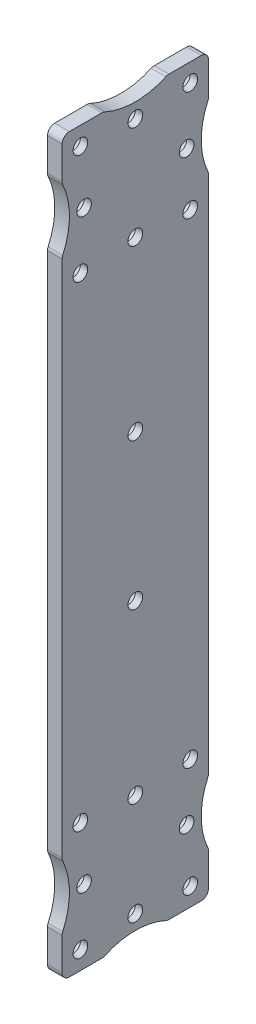
SolidWorks part; units mm, degrees
ref_plane "前视基准面" through (0, 0, 0) normal (0, 0, 1) x (1, 0, 0)
ref_plane "上视基准面" through (0, 0, 0) normal (0, 1, 0) x (1, 0, 0)
ref_plane "右视基准面" through (0, 0, 0) normal (1, 0, 0) x (0, 0, -1)
sketch "草图1" plane through (0, 0, 0) normal (1, 0, 0) x (0, 0, -1)
  line L0 (0, 50) -> (20, 50) construction
  line L1 (0, 0) -> (20, 0)
  line L2 (0, 0) -> (0, 100)
  line L3 (0, 100) -> (20, 100)
  line L4 (20, 0) -> (20, 100)
  circle A0 centre (2.5, 97.5) radius 1
  circle A1 centre (17.5, 97.5) radius 1
  circle A2 centre (17.5, 82.5) radius 1
  circle A3 centre (2.5, 82.5) radius 1
  circle A4 centre (17.5, 17.5) radius 1
  circle A5 centre (2.5, 17.5) radius 1
  circle A6 centre (2.5, 2.5) radius 1
  circle A7 centre (17.5, 2.5) radius 1
  dimension "D3" = 2
  dimension "D4" = 2
  dimension "D5" = 2.5
  dimension "D6" = 2.5
  dimension "D7" = 2.5
  dimension "D8" = 15
  dimension "D1" = 20
  dimension "D2" = 100
  dimension "D9" = 2
extrude "凸台-拉伸1" add sketch "草图1" along normal blind 2
ref_plane "基准面1" through (0, 50, 0) normal (0, -1, 0) x (-1, 0, 0)
sketch "草图3" plane through (2, 0, 0) normal (1, 0, 0) x (0, 0, -1)
  line L0 (20, 100) -> (0, 100) construction
  line L1 (20, 0) -> (20, 100) construction
  line L2 (0, 100) -> (0, 0) construction
  circle A0 centre (10, 109) radius 10
  circle A1 centre (-9, 90) radius 10
  circle A2 centre (29, 90) radius 10
  dimension "D1" = 20
  dimension "D2" = 9
  dimension "D3" = 10
  dimension "D4" = 20
  dimension "D5" = 20
  dimension "D6" = 10
  dimension "D7" = 9
  dimension "D8" = 9
  dimension "D9" = 10
extrude "切除-拉伸2" cut sketch "草图3" against normal blind 10
mirror "镜向2" about plane through (0, 50, 0) normal (0, -1, 0) of "切除-拉伸2"
sketch "草图4" plane through (2, 0, 0) normal (1, 0, 0) x (0, 0, -1)
  line L0 (5.6411, 100) -> (0, 100) construction
  line L1 (0, 100) -> (0, 94.3589) construction
  line L2 (20, 100) -> (14.3589, 100) construction
  line L3 (20, 94.3589) -> (20, 100) construction
  line L4 (0, 100) -> (0, 94.3589) construction
  circle A0 centre (10, 97) radius 1
  circle A1 centre (3, 90) radius 1
  circle A2 centre (17, 90) radius 1
  circle A3 centre (10, 83) radius 1
  dimension "D1" = 2
  dimension "D2" = 3
  dimension "D3" = 10
  dimension "D4" = 2
  dimension "D5" = 2
  dimension "D6" = 2
  dimension "D7" = 10
  dimension "D8" = 10
  dimension "D9" = 14
  dimension "D10" = 10
  dimension "D11" = 14
  dimension "D12" = 3
extrude "切除-拉伸3" cut sketch "草图4" against normal blind 10
mirror "镜向3" about plane through (0, 50, 0) normal (0, -1, 0) of "切除-拉伸3"
fillet "圆角2" radius 1 16 edges at (1, 0, -20) (1, 0, -5.6411) (1, 0, -14.3589) (1, 0, 0) (1, 5.6411, -20) (1, 14.3589, -20) (1, 14.3589, 0) (1, 5.6411, 0) (1, 94.3589, -20) (1, 85.6411, -20) (1, 85.6411, 0) (1, 94.3589, 0) (1, 100, -20) (1, 100, -5.6411) (1, 100, -14.3589) (1, 100, 0)
sketch "草图5" plane through (0, 0, 0) normal (-1, 0, 0) x (0, 0, 1)
  line L0 (-20, 14.5826) -> (-20, 85.4174) construction
  circle A0 centre (-10, 60) radius 1
  circle A1 centre (-10, 40) radius 1
  point P2 (-20, 50)
  dimension "D1" = 2
  dimension "D3" = 2
  dimension "D2" = 10
  dimension "D4" = 20
extrude "切除-拉伸4" cut sketch "草图5" against normal through all
sketch "草图6" plane through (0, 0, 0) normal (-1, 0, 0) x (0, 0, 1)
  circle A0 centre (-2.5, 97.5) radius 1.5
  circle A1 centre (-3, 90) radius 1.5
  circle A2 centre (-2.5, 82.5) radius 1.5
  circle A3 centre (-10, 97) radius 1.5
  circle A4 centre (-10, 83) radius 1.5
  circle A5 centre (-17.5, 97.5) radius 1.5
  circle A6 centre (-17, 90) radius 1.5
  circle A7 centre (-17.5, 82.5) radius 1.5
  circle A8 centre (-10, 60) radius 1.5
  circle A9 centre (-10, 40) radius 1.5
  circle A10 centre (-2.5, 17.5) radius 1.5
  circle A11 centre (-3, 10) radius 1.5
  circle A12 centre (-2.5, 2.5) radius 1.5
  circle A13 centre (-10, 17) radius 1.5
  circle A14 centre (-10, 3) radius 1.5
  circle A15 centre (-17.5, 17.5) radius 1.5
  circle A16 centre (-17, 10) radius 1.5
  circle A17 centre (-17.5, 2.5) radius 1.5
  dimension "D1" = 3
  dimension "D2" = 3
  dimension "D3" = 3
  dimension "D4" = 3
  dimension "D5" = 3
  dimension "D6" = 3
  dimension "D7" = 3
  dimension "D8" = 3
  dimension "D9" = 3
  dimension "D10" = 3
  dimension "D11" = 3
  dimension "D12" = 3
  dimension "D13" = 3
  dimension "D14" = 3
  dimension "D15" = 3
  dimension "D16" = 3
  dimension "D17" = 3
  dimension "D18" = 3
extrude "切除-拉伸5" cut sketch "草图6" against normal blind 1
